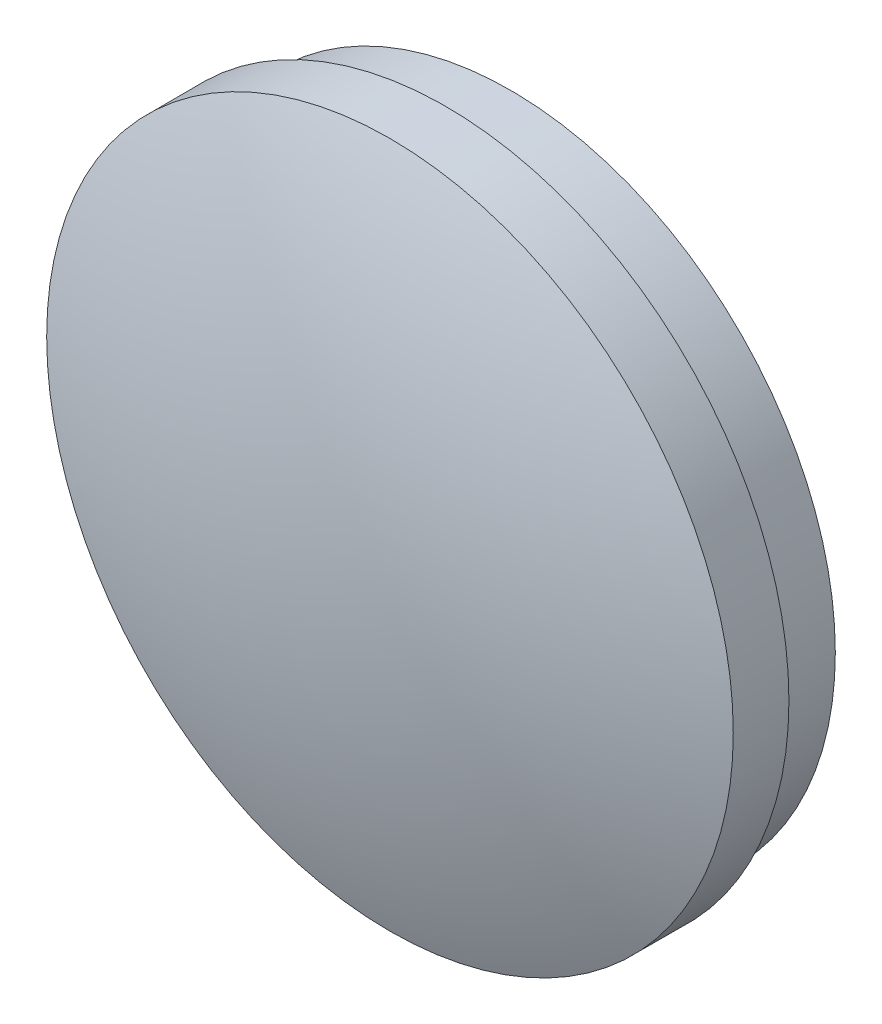
SolidWorks part; units mm, degrees
material "1.0553 (S355J0)"
ref_plane "XY Plane" through (0, 0, 0) normal (0, 0, 1) x (1, 0, 0)
ref_plane "XZ Plane" through (0, 0, 0) normal (0, 1, 0) x (1, 0, 0)
ref_plane "YZ Plane" through (0, 0, 0) normal (1, 0, 0) x (0, 0, -1)
sketch "Sketch1" plane through (0, 0, 0) normal (1, 0, 0) x (0, 0, -1)
  line L0 (8, 0) -> (8, 6)
  line L1 (8, 6) -> (0, 6)
  line L2 (0, 6) -> (0, 17.5)
  line L3 (0, 17.5) -> (-3.5, 17.5)
  line L6 (-10, 0) -> (8, 0)
  line L7 (0, 0) -> (0, 6) construction
  line L8 (8, 0) -> (37.5276, 0) construction
  line L9 (-3.5, 17.5) -> (-3.5, 18.5)
  line L10 (-3.5, 18.5) -> (-6.5, 18.5)
  arc A0 (-6.5, 18.5) -> (-10, 0) centre (40.6429, 0) ccw
  dimension "D1" = 12
  dimension "D2" = 35
  dimension "D3" = 37
  dimension "D4" = 8
  dimension "D5" = 18
  dimension "D6" = 6.5
  dimension "D7" = 3.5
revolve "Revolve1" add sketch "Sketch1" angle 360 about L8
